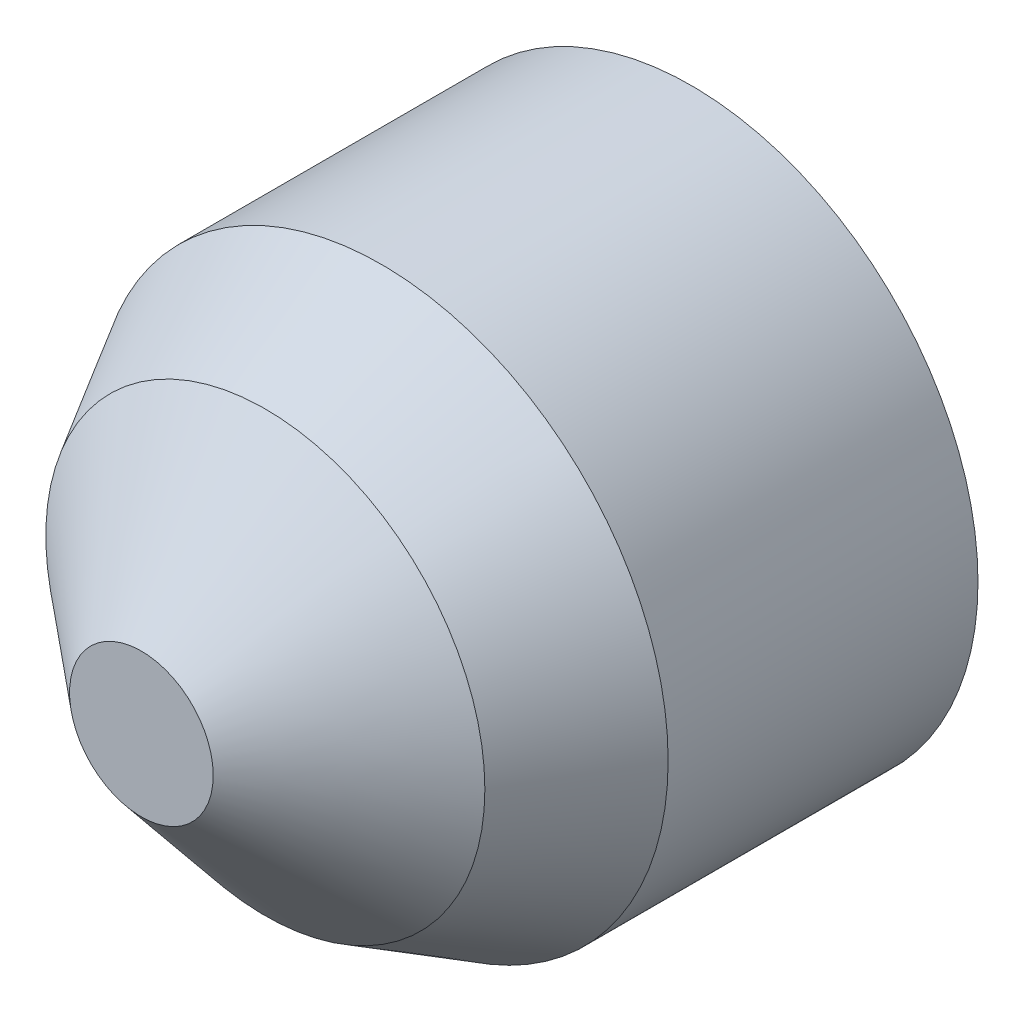
SolidWorks part; units mm, degrees
ref_plane "Front Plane" through (0, 0, 0) normal (0, 0, 1) x (1, 0, 0)
ref_plane "Top Plane" through (0, 0, 0) normal (0, 1, 0) x (1, 0, 0)
ref_plane "Right Plane" through (0, 0, 0) normal (1, 0, 0) x (0, 0, -1)
sketch "Sketch1" plane through (0, 0, 0) normal (0, 0, 1) x (1, 0, 0)
  circle A0 centre (0, 0) radius 7.4
extrude "Lens_body" add sketch "Sketch1" along normal blind 8
ref_plane "Plane_Z+8.00" through (0, 0, 8) normal (0, 0, 1) x (1, 0, 0)
sketch "Sketch2" plane through (0, 0, 8) normal (0, 0, 1) x (1, 0, 0)
  circle A0 centre (0, 0) radius 7.4
extrude "Lens_shoulder" add sketch "Sketch2" along normal blind 3 draft 30
ref_plane "Plane_Z+11.00" through (0, 0, 11) normal (0, 0, 1) x (1, 0, 0)
sketch "Sketch3" plane through (0, 0, 11) normal (0, 0, 1) x (1, 0, 0)
  circle A0 centre (0, 0) radius 5.6679
extrude "Lens_crown" add sketch "Sketch3" along normal blind 3.2 draft 50
ref_plane "Plane_Z+4.25" through (0, 0, 4.25) normal (0, 0, 1) x (1, 0, 0)
sketch "Sketch4" plane through (0, 0, 4.25) normal (0, 0, 1) x (1, 0, 0)
  circle A0 centre (0, 0) radius 2.6
  dimension "LedPressFit" = 5.2
extrude "LED_cavity" cut sketch "Sketch4" against normal mid plane 9.5
